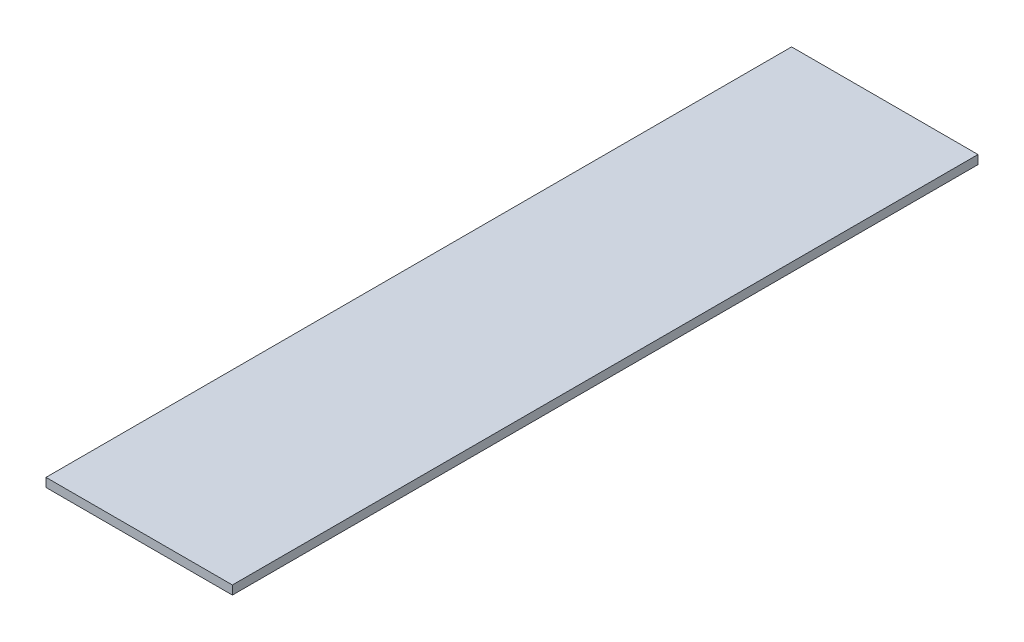
SolidWorks part; units mm, degrees
ref_plane "Front Plane" through (0, 0, 0) normal (0, 0, 1) x (1, 0, 0)
ref_plane "Top Plane" through (0, 0, 0) normal (0, 1, 0) x (1, 0, 0)
ref_plane "Right Plane" through (0, 0, 0) normal (1, 0, 0) x (0, 0, -1)
sketch "Sketch1" plane through (0, 0, 0) normal (0, 1, 0) x (1, 0, 0)
  line L1 (-12.5, -50) -> (12.5, -50)
  line L2 (-12.5, -50) -> (-12.5, 50)
  line L3 (-12.5, 50) -> (12.5, 50)
  line L4 (12.5, -50) -> (12.5, 50)
  line L5 (-12.5, -50) -> (12.5, 50) construction
  line L6 (-12.5, 50) -> (12.5, -50) construction
  point P0 (0, 0)
  dimension "D1" = 25
  dimension "D2" = 100
extrude "Boss-Extrude1" add sketch "Sketch1" along normal blind 1.18
